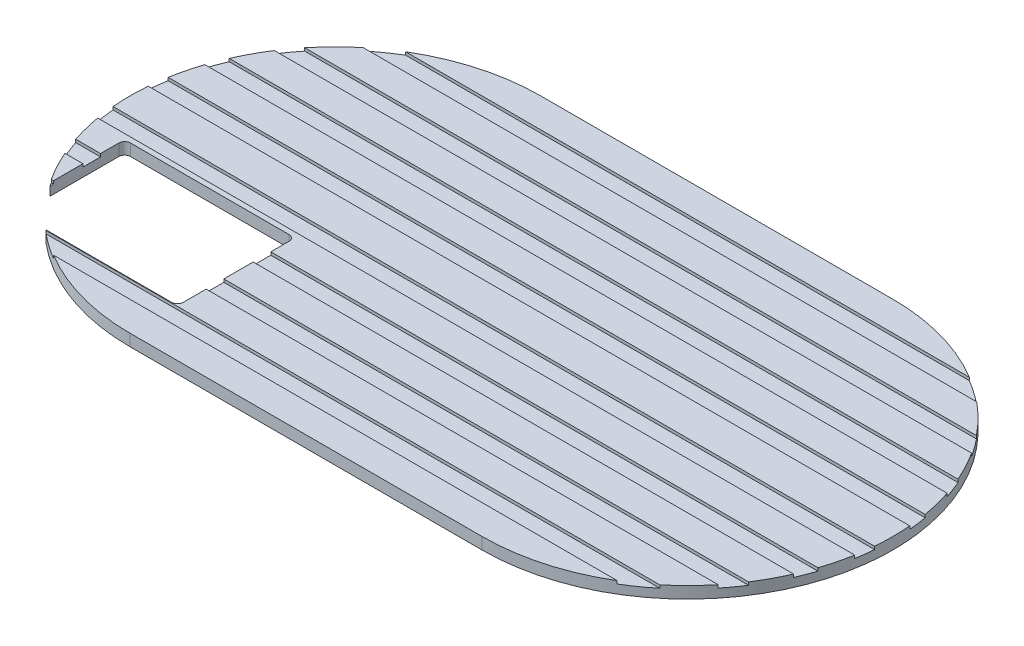
SolidWorks part; units mm, degrees
material "Oak"
ref_plane "Front Plane" through (0, 0, 0) normal (0, 0, 1) x (1, 0, 0)
ref_plane "Top Plane" through (0, 0, 0) normal (0, 1, 0) x (1, 0, 0)
ref_plane "Right Plane" through (0, 0, 0) normal (1, 0, 0) x (0, 0, -1)
sketch "Sketch1" plane through (0, 0, 0) normal (0, 1, 0) x (1, 0, 0)
  line L0 (0, 35) -> (-60, 35)
  line L1 (0, -35) -> (-60, -35)
  arc A0 (0, -35) -> (0, 35) centre (0, 0) ccw
  arc A1 (-60, 35) -> (-60, -35) centre (-60, 0) ccw
extrude "Boss-Extrude1" add sketch "Sketch1" along normal blind 2
sketch "Sketch2" plane through (0, 2, 0) normal (0, 1, 0) x (1, 0, 0)
  line L0 (-30, 35) -> (-30, -35) construction
  line L1 (0, 35) -> (-60, 35) construction
  line L2 (-60, -35) -> (0, -35) construction
  line L3 (-97.6347, 30) -> (39.6516, 30) construction
  line L4 (-99.3827, 27) -> (39.6516, 27) construction
  line L5 (-85.802, 30) -> (25.1297, 30)
  line L6 (25.1297, 30) -> (25.1297, 27)
  line L7 (25.1297, 27) -> (-85.802, 27)
  line L8 (-85.802, 30) -> (-85.802, 27)
  line L9 (-99.3827, 0) -> (43.4166, 0) construction
  line L14 (-99.3827, 22) -> (39.6516, 22) construction
  line L15 (-97.6347, 19) -> (35.8867, 19) construction
  line L16 (-92.2562, 22) -> (-92.2562, 19)
  line L17 (-92.2562, 19) -> (32.2562, 19)
  line L18 (32.2562, 19) -> (32.2562, 22)
  line L19 (32.2562, 22) -> (-92.2562, 22)
  line L20 (-114.1736, 14) -> (39.6516, 14) construction
  line L21 (-99.3827, 11) -> (37.3658, 11) construction
  line L22 (-95.6178, 14) -> (-95.6178, 11)
  line L23 (-95.6178, 11) -> (35.8867, 11)
  line L24 (35.8867, 11) -> (35.8867, 14)
  line L25 (35.8867, 14) -> (-95.6178, 14)
  line L26 (-101.3997, 6) -> (40.8618, 6) construction
  line L27 (-99.3827, 3) -> (40.8618, 3) construction
  line L28 (-95.6178, 6) -> (-95.6178, 3)
  line L29 (-95.6178, 3) -> (38.307, 3)
  line L30 (38.307, 3) -> (38.307, 6)
  line L31 (38.307, 6) -> (-95.6178, 6)
  line L32 (38.307, -3) -> (38.307, -6)
  line L33 (-95.6178, -3) -> (38.307, -3)
  line L34 (-95.6178, -6) -> (-95.6178, -3)
  line L35 (38.307, -6) -> (-95.6178, -6)
  line L36 (35.8867, -11) -> (35.8867, -14)
  line L37 (-95.6178, -11) -> (35.8867, -11)
  line L38 (-95.6178, -14) -> (-95.6178, -11)
  line L39 (35.8867, -14) -> (-95.6178, -14)
  line L40 (32.2562, -19) -> (32.2562, -22)
  line L41 (-92.2562, -19) -> (32.2562, -19)
  line L42 (-92.2562, -22) -> (-92.2562, -19)
  line L43 (32.2562, -22) -> (-92.2562, -22)
  line L44 (-85.802, -30) -> (25.1297, -30)
  line L45 (25.1297, -30) -> (25.1297, -27)
  line L46 (25.1297, -27) -> (-85.802, -27)
  line L47 (-85.802, -30) -> (-85.802, -27)
  dimension "D1" = 5
  dimension "D2" = 3
  dimension "D3" = 5
  dimension "D4" = 3
  dimension "D5" = 5
  dimension "D6" = 3
  dimension "D7" = 5
  dimension "D8" = 3
extrude "Cut-Extrude1" cut sketch "Sketch2" against normal blind 0.5
sketch "Sketch3" plane through (0, 0, 0) normal (0, 1, 0) x (1, 0, 0)
  line L0 (-60, -26.8925) -> (-60, -6.8925)
  line L2 (-89, -26.8925) -> (-60, -26.8925) construction
  line L8 (-89, -6.8925) -> (-89, -26.8925) construction
  line L9 (-60, -6.8925) -> (-89, -6.8925)
  line L10 (-89, -6.8925) -> (-89, -26.8925)
  line L11 (-89, -26.8925) -> (-60, -26.8925)
  line L12 (-89, -6.8925) -> (-60, -6.8925) construction
  dimension "D1" = 29
  dimension "D2" = 20
extrude "Cut-Extrude3" cut sketch "Sketch3" along normal through all and the other way through all
fillet "Fillet1" radius 1 3 edges at (-60, 1, 26.8925) (-60, 1, 6.8925) (-89, 1, 6.8925)
